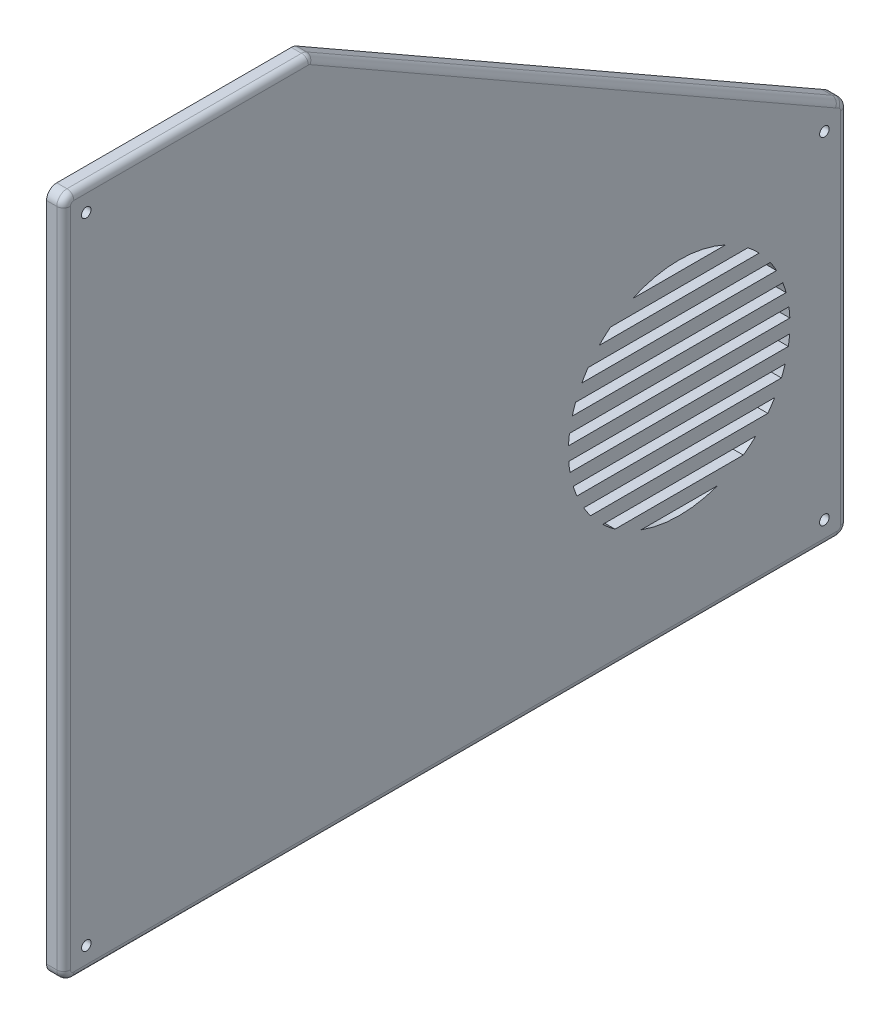
SolidWorks part; units mm, degrees
ref_plane "Front Plane" through (0, 0, 0) normal (0, 0, 1) x (1, 0, 0)
ref_plane "Top Plane" through (0, 0, 0) normal (0, 1, 0) x (1, 0, 0)
ref_plane "Right Plane" through (0, 0, 0) normal (1, 0, 0) x (0, 0, -1)
sketch "Sketch2" plane through (0, 0, 0) normal (1, 0, 0) x (0, 0, -1)
  line L0 (-137.0535, 114.0413) -> (-137.0535, -79.9587)
  line L1 (-134.0535, -82.9587) -> (89.9465, -82.9587)
  line L2 (92.9465, -79.9587) -> (92.9465, 25.3682)
  line L3 (91.4359, 27.9724) -> (90.4288, 28.5483)
  line L4 (90.4288, 28.5483) -> (-63.748, 116.6461)
  line L5 (-65.2364, 117.0413) -> (-134.0535, 117.0413)
  circle A0 centre (-130.4022, 110.1643) radius 1.4
  circle A1 centre (-130.3788, -76.1025) radius 1.4
  circle A2 centre (86.1788, -76.1909) radius 1.4141
  circle A3 centre (86.1788, 22.4402) radius 1.4
  arc A4 (-137.0535, -79.9587) -> (-134.0535, -82.9587) centre (-134.0535, -79.9587) ccw
  arc A5 (89.9465, -82.9587) -> (92.9465, -79.9587) centre (89.9465, -79.9587) ccw
  arc A6 (92.9465, 25.3682) -> (91.4359, 27.9724) centre (89.9465, 25.3682) ccw
  arc A7 (-63.748, 116.6461) -> (-65.2364, 117.0413) centre (-65.2364, 114.0413) ccw
  arc A8 (-134.0535, 117.0413) -> (-137.0535, 114.0413) centre (-134.0535, 114.0413) ccw
extrude "Boss-Extrude2" add sketch "Sketch2" along normal blind 5
sketch "Sketch3" plane through (5, 0, 0) normal (1, 0, 0) x (0, 0, -1)
  line L0 (5.7344, 1.1421) -> (80.9473, 1.1421)
  line L1 (5.7344, 11.1421) -> (80.9473, 11.1421)
  line L2 (5.7344, 11.1421) -> (5.7344, 8.1421)
  line L3 (5.7344, 8.1421) -> (80.9473, 8.1421)
  line L4 (80.9473, 11.1421) -> (80.9473, 8.1421)
  line L5 (5.7344, 4.1421) -> (80.9473, 4.1421)
  line L6 (5.7344, 4.1421) -> (5.7344, 1.1421)
  line L7 (80.9473, 4.1421) -> (80.9473, 1.1421)
  line L8 (5.7344, -5.8579) -> (80.9473, -5.8579)
  line L9 (5.7344, -2.8579) -> (80.9473, -2.8579)
  line L10 (5.7344, -2.8579) -> (5.7344, -5.8579)
  line L11 (80.9473, -2.8579) -> (80.9473, -5.8579)
  line L12 (5.7344, -12.8579) -> (80.9473, -12.8579)
  line L13 (5.7344, -9.8579) -> (80.9473, -9.8579)
  line L14 (5.7344, -9.8579) -> (5.7344, -12.8579)
  line L15 (80.9473, -9.8579) -> (80.9473, -12.8579)
  line L16 (5.7344, -19.8579) -> (80.9473, -19.8579)
  line L17 (5.7344, -16.8579) -> (80.9473, -16.8579)
  line L18 (5.7344, -16.8579) -> (5.7344, -19.8579)
  line L19 (80.9473, -16.8579) -> (80.9473, -19.8579)
  line L20 (5.7344, -26.8579) -> (80.9473, -26.8579)
  line L21 (5.7344, -23.8579) -> (80.9473, -23.8579)
  line L22 (5.7344, -23.8579) -> (5.7344, -26.8579)
  line L23 (80.9473, -23.8579) -> (80.9473, -26.8579)
  line L24 (5.7344, -33.8579) -> (80.9473, -33.8579)
  line L25 (5.7344, -30.8579) -> (80.9473, -30.8579)
  line L26 (5.7344, -30.8579) -> (5.7344, -33.8579)
  line L27 (80.9473, -30.8579) -> (80.9473, -33.8579)
  line L28 (5.7344, -40.8579) -> (80.9473, -40.8579)
  line L29 (5.7344, -37.8579) -> (80.9473, -37.8579)
  line L30 (5.7344, -37.8579) -> (5.7344, -40.8579)
  line L31 (80.9473, -37.8579) -> (80.9473, -40.8579)
  line L32 (5.7344, -47.8579) -> (80.9473, -47.8579)
  line L33 (5.7344, -44.8579) -> (80.9473, -44.8579)
  line L34 (5.7344, -44.8579) -> (5.7344, -47.8579)
  line L35 (80.9473, -44.8579) -> (80.9473, -47.8579)
  line L36 (5.7344, -54.8579) -> (80.9473, -54.8579)
  line L37 (5.7344, -51.8579) -> (80.9473, -51.8579)
  line L38 (5.7344, -51.8579) -> (5.7344, -54.8579)
  line L39 (80.9473, -51.8579) -> (80.9473, -54.8579)
  circle A0 centre (43.568, -21.3579) radius 32.5
  dimension "D1" = 65
  dimension "D2" = 3
  dimension "D3" = 10
extrude "Cut-Extrude1" cut sketch "Sketch3" against normal blind 5 contours L3 A0 | L0 A0 L5 | L8 A0 L9 | L12 A0 L13 | L16 A0 L17 | L21 A0 L20 | L25 A0 L24 | L29 A0 L28 | L33 A0 L32 | L37 A0
fillet "Fillet4" radius 2 11 edges at (5, 116.1626, 136.1748) (5, 116.9408, 64.4664) (5, 117.0413, 99.6449) (5, -82.08, 136.1748) (5, 17.0413, 137.0535) (5, -82.9587, 22.0535) (5, -82.08, -92.0679) (5, 28.2603, -90.9323) (5, 26.8735, -92.5415) (5, -27.2953, -92.9465) (5, 72.5972, -13.3404)
